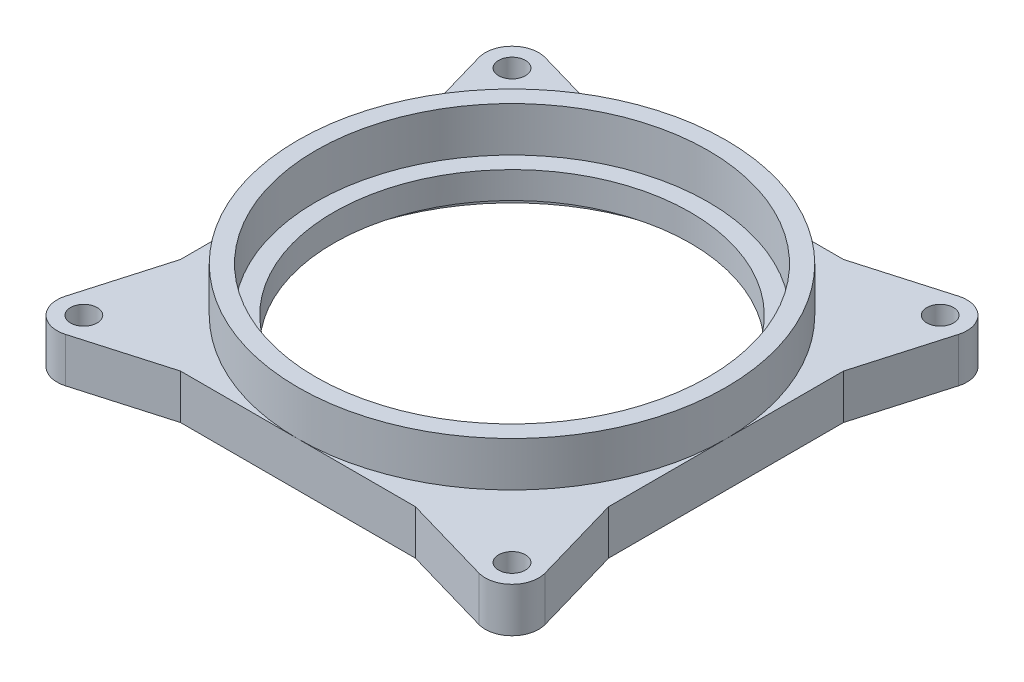
SolidWorks part; units mm, degrees
ref_plane "Front Plane" through (0, 0, 0) normal (0, 0, 1) x (1, 0, 0)
ref_plane "Top Plane" through (0, 0, 0) normal (0, 1, 0) x (1, 0, 0)
ref_plane "Right Plane" through (0, 0, 0) normal (1, 0, 0) x (0, 0, -1)
sketch "Sketch1" plane through (0, 0, 0) normal (0, 1, 0) x (1, 0, 0)
  line L0 (0, -68.4392) -> (0, 68.4392) construction
  line L1 (-24, -24) -> (24, -24)
  line L2 (-24, -24) -> (-24, 24)
  line L3 (-24, 24) -> (24, 24)
  line L4 (24, -24) -> (24, 24)
  line L5 (-24, -24) -> (24, 24) construction
  line L6 (-24, 24) -> (24, -24) construction
  line L7 (-78.6119, 0) -> (78.6119, 0) construction
  line L8 (23.169, 26.8826) -> (13.169, 24)
  line L9 (26.8826, 23.169) -> (24, 13.169)
  line L10 (23.169, -26.8826) -> (13.169, -24)
  line L11 (26.8826, -23.169) -> (24, -13.169)
  line L12 (-23.169, 26.8826) -> (-13.169, 24)
  line L13 (-26.8826, 23.169) -> (-24, 13.169)
  line L14 (-26.8826, -23.169) -> (-24, -13.169)
  line L15 (-23.169, -26.8826) -> (-13.169, -24)
  circle A0 centre (0, 0) radius 22.5
  circle A1 centre (24, 24) radius 1.5
  circle A2 centre (24, 24) radius 3
  circle A3 centre (24, -24) radius 1.5
  circle A4 centre (24, -24) radius 3
  circle A5 centre (-24, 24) radius 1.5
  circle A6 centre (-24, 24) radius 3
  circle A7 centre (-24, -24) radius 1.5
  circle A8 centre (-24, -24) radius 3
  point P0 (0, 0)
  point P13 (0, 0)
  point P16 (0, 0)
  dimension "D3" = 45
  dimension "D4" = 3
  dimension "D5" = 6
  dimension "D1" = 48
  dimension "D2" = 48
  dimension "D6" = 10
  dimension "D7" = 10
extrude "Boss-Extrude1" add sketch "Sketch1" along normal blind 25 contours A8 L1 A4 L4 A2 L3 A6 L2 A0 | L10 A4 L1 | L4 A4 L11 | A4 L4 A3 L1 | A4 L1 A3 L4 | L4 A2 L3 A1 | A2 L4 L9 | L3 A2 L4 A1 | A2 L8 L3 | A6 L2 A5 L3 | L12 A6 L3 | A6 L3 A5 L2 | L2 A6 L13 | A8 L15 L1 | L1 A8 L2 A7 | A8 L1 A7 L2 | A8 L2 L14 | A0
sketch "Sketch2" plane through (0, 0, 0) normal (0, -1, 0) x (1, 0, 0)
  circle A0 centre (0, 0) radius 20
  dimension "D1" = 40
extrude "Cut-Extrude1" cut sketch "Sketch2" against normal blind 23
sketch "Sketch3" plane through (0, 25, 0) normal (0, 1, 0) x (1, 0, 0)
  line L12 (24, 13.169) -> (26.8826, 23.169)
  line L13 (23.169, 26.8826) -> (13.169, 24)
  line L14 (13.169, 24) -> (-13.169, 24)
  line L15 (-13.169, 24) -> (-23.169, 26.8826)
  line L16 (-26.8826, 23.169) -> (-24, 13.169)
  line L17 (-24, 13.169) -> (-24, -13.169)
  line L18 (-24, -13.169) -> (-26.8826, -23.169)
  line L19 (-23.169, -26.8826) -> (-13.169, -24)
  line L20 (-13.169, -24) -> (13.169, -24)
  line L21 (13.169, -24) -> (23.169, -26.8826)
  line L22 (26.8826, -23.169) -> (24, -13.169)
  line L23 (24, -13.169) -> (24, 13.169)
  line L24 (24, 13.169) -> (26.8826, 23.169)
  line L25 (23.169, 26.8826) -> (13.169, 24)
  line L26 (13.169, 24) -> (-13.169, 24)
  line L27 (-13.169, 24) -> (-23.169, 26.8826)
  line L28 (-26.8826, 23.169) -> (-24, 13.169)
  line L29 (-24, 13.169) -> (-24, -13.169)
  line L30 (-24, -13.169) -> (-26.8826, -23.169)
  line L31 (-23.169, -26.8826) -> (-13.169, -24)
  line L32 (-13.169, -24) -> (13.169, -24)
  line L33 (13.169, -24) -> (23.169, -26.8826)
  line L34 (26.8826, -23.169) -> (24, -13.169)
  line L35 (24, -13.169) -> (24, 13.169)
  circle A0 centre (0, 0) radius 24
  arc A4 (26.8826, 23.169) -> (23.169, 26.8826) centre (24, 24) ccw
  arc A5 (-23.169, 26.8826) -> (-26.8826, 23.169) centre (-24, 24) ccw
  arc A6 (-26.8826, -23.169) -> (-23.169, -26.8826) centre (-24, -24) ccw
  arc A7 (23.169, -26.8826) -> (26.8826, -23.169) centre (24, -24) ccw
  arc A8 (26.8826, 23.169) -> (23.169, 26.8826) centre (24, 24) ccw
  arc A9 (-23.169, 26.8826) -> (-26.8826, 23.169) centre (-24, 24) ccw
  arc A10 (-26.8826, -23.169) -> (-23.169, -26.8826) centre (-24, -24) ccw
  arc A11 (23.169, -26.8826) -> (26.8826, -23.169) centre (24, -24) ccw
  circle M17 centre (-24, -24) radius 1.5
  circle M18 centre (24, -24) radius 1.5
  line M19 (24, 13.169) -> (26.8826, 23.169)
  arc M20 (26.8826, 23.169) -> (23.169, 26.8826) centre (24, 24) ccw
  line M21 (23.169, 26.8826) -> (13.169, 24)
  line M22 (13.169, 24) -> (-13.169, 24)
  line M23 (-13.169, 24) -> (-23.169, 26.8826)
  arc M24 (-23.169, 26.8826) -> (-26.8826, 23.169) centre (-24, 24) ccw
  line M25 (-26.8826, 23.169) -> (-24, 13.169)
  line M26 (-24, 13.169) -> (-24, -13.169)
  line M27 (-24, -13.169) -> (-26.8826, -23.169)
  arc M28 (-26.8826, -23.169) -> (-23.169, -26.8826) centre (-24, -24) ccw
  line M29 (-23.169, -26.8826) -> (-13.169, -24)
  line M30 (-13.169, -24) -> (13.169, -24)
  line M31 (13.169, -24) -> (23.169, -26.8826)
  arc M32 (23.169, -26.8826) -> (26.8826, -23.169) centre (24, -24) ccw
  line M33 (26.8826, -23.169) -> (24, -13.169)
  line M34 (24, -13.169) -> (24, 13.169)
  circle M35 centre (24, 24) radius 1.5
  circle M36 centre (-24, 24) radius 1.5
  dimension "D1" = 0
extrude "Cut-Extrude2" cut sketch "Sketch3" against normal blind 20 contours A0 L26 M23 M24 M25 M26 M36 | A0 L29 M27 M28 M29 M30 M17 | A0 L32 M31 M32 M33 M34 M18 | A0 L35 M19 M20 M21 M22 M35
fillet "Fillet2" radius 3 1 edges at (0, 23, -20)
sketch "Sketch4" plane through (0, 0, 0) normal (0, -1, 0) x (1, 0, 0)
  circle A0 centre (0, 0) radius 22.5
  circle A1 centre (0, 0) radius 20 construction
  circle A2 centre (0, 0) radius 20
  dimension "D1" = 45
extrude "Cut-Extrude3" cut sketch "Sketch4" against normal blind 2
sketch "Sketch5" plane through (0, 25, 0) normal (0, 1, 0) x (1, 0, 0)
  circle A1 centre (0, 0) radius 24
  circle A2 centre (0, 0) radius 24
  dimension "D1" = 0
extrude "Cut-Extrude4" cut sketch "Sketch5" against normal blind 15
sketch "Sketch6" plane through (0, 10, 0) normal (0, 1, 0) x (1, 0, 0)
  circle A0 centre (0, 0) radius 22
  dimension "D1" = 44
extrude "Cut-Extrude5" cut sketch "Sketch6" against normal blind 5
